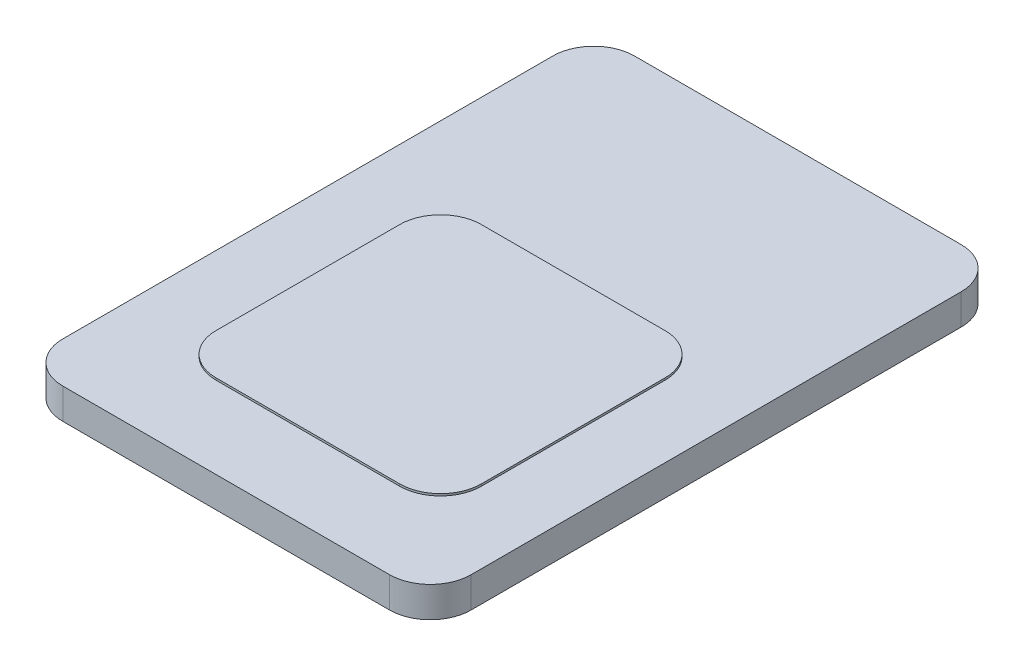
SolidWorks part; units mm, degrees
ref_plane "Front Plane" through (0, 0, 0) normal (0, 0, 1) x (1, 0, 0)
ref_plane "Top Plane" through (0, 0, 0) normal (0, 1, 0) x (1, 0, 0)
ref_plane "Right Plane" through (0, 0, 0) normal (1, 0, 0) x (0, 0, -1)
sketch "Sketch1" plane through (0, 0, 0) normal (0, 1, 0) x (1, 0, 0)
  line L1 (0, 0) -> (20, 0)
  line L2 (0, 0) -> (0, 28)
  line L3 (0, 28) -> (20, 28)
  line L4 (20, 0) -> (20, 28)
  line L5 (0, 0) -> (20, 28) construction
  line L6 (0, 28) -> (20, 0) construction
  point P4 (10, 14)
  dimension "D1" = 28
  dimension "D2" = 20
extrude "Boss-Extrude1" add sketch "Sketch1" along normal blind 1.5
sketch "Sketch2" plane through (0, 1.5, 0) normal (0, 1, 0) x (1, 0, 0)
  line L0 (20, 0) -> (20, 28) construction
  line L1 (5.5, 17) -> (14.5, 17)
  line L2 (3.5, 15) -> (3.5, 6)
  line L3 (5.5, 4) -> (14.5, 4)
  line L4 (16.5, 15) -> (16.5, 6)
  line L5 (3.5, 17) -> (16.5, 4) construction
  line L6 (3.5, 4) -> (16.5, 17) construction
  line L7 (0, 0) -> (20, 0) construction
  arc A0 (3.5, 6) -> (5.5, 4) centre (5.5, 6) ccw
  arc A1 (16.5, 6) -> (14.5, 4) centre (14.5, 6) cw
  arc A2 (3.5, 15) -> (5.5, 17) centre (5.5, 15) cw
  arc A3 (14.5, 17) -> (16.5, 15) centre (14.5, 15) cw
  point P4 (10, 10.5)
  dimension "D5" = 2
  dimension "D1" = 13
  dimension "D2" = 13
  dimension "D3" = 3.5
  dimension "D4" = 4
extrude "Boss-Extrude2" add sketch "Sketch2" along normal blind 0.1
fillet "Fillet1" radius 2 4 edges at (20, 0.75, 0) (0, 0.75, 0) (0, 0.75, -28) (20, 0.75, -28)
